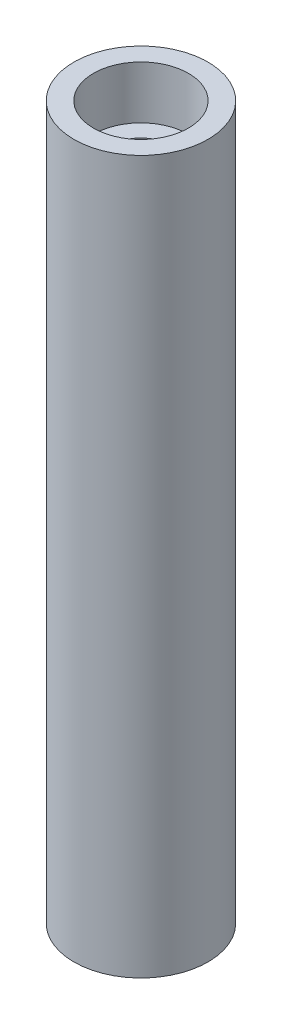
SolidWorks part; units mm, degrees
ref_plane "Front Plane" through (0, 0, 0) normal (0, 0, 1) x (1, 0, 0)
ref_plane "Top Plane" through (0, 0, 0) normal (0, 1, 0) x (1, 0, 0)
ref_plane "Right Plane" through (0, 0, 0) normal (1, 0, 0) x (0, 0, -1)
sketch "Sketch1" plane through (0, 0, 0) normal (0, 1, 0) x (1, 0, 0)
  circle A0 centre (0, 0) radius 12.7
  dimension "D1" = 25.4
extrude "Boss-Extrude1" add sketch "Sketch1" along normal blind 135
sketch "Sketch2" plane through (0, 135, 0) normal (0, 1, 0) x (1, 0, 0)
  point P0 (0, 0)
hole_wizard "CBORE for M10 SHCS1" positions "Sketch2" profile "Sketch4" counterbore size "M10" standard "ANSI Metric" end condition through all
sketch "Sketch4" plane through (0, 135, 0) normal (1, 0, 0) x (0, 0, 1)
  line L0 (0, 0) -> (0, 135)
  line L1 (0, 135) -> (5.5, 135)
  line L3 (5.5, 135) -> (5.5, 10)
  line L4 (5.5, 10) -> (9, 10)
  line L5 (9, 10) -> (9, 0)
  line L7 (9, 0) -> (0, 0)
  line L11 (0, -6.35) -> (0, 107.95) construction
  dimension "Thru Hole Dia." = 11
  dimension "Thru Hole Depth" = 135
  dimension "C'Bore Dia." = 18
  dimension "C'Bore Depth" = 10
